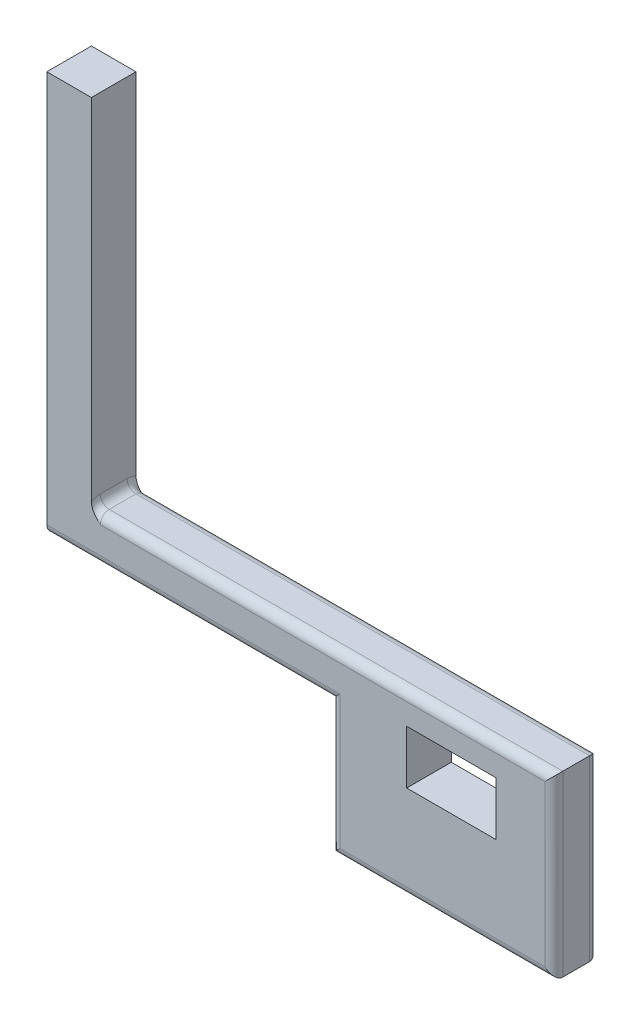
SolidWorks part; units mm, degrees
material "PE High Density"
ref_plane "Front Plane" through (0, 0, 0) normal (0, 0, 1) x (1, 0, 0)
ref_plane "Top Plane" through (0, 0, 0) normal (0, 1, 0) x (1, 0, 0)
ref_plane "Right Plane" through (0, 0, 0) normal (1, 0, 0) x (0, 0, -1)
sketch "Sketch1" plane through (0, 0, 0) normal (0, 1, 0) x (1, 0, 0)
  line L1 (0, 0) -> (5, 0)
  line L2 (0, 0) -> (0, 5)
  line L3 (0, 5) -> (5, 5)
  line L4 (5, 0) -> (5, 5)
  dimension "D1" = 5
  dimension "D2" = 5
extrude "Boss-Extrude1" add sketch "Sketch1" along normal blind 40
sketch "Sketch2" plane through (0, 0, 0) normal (0, -1, 0) x (1, 0, 0)
  line L0 (0, 0) -> (56.86, 0)
  line L1 (56.86, -5) -> (0, -5)
  line L2 (0, 0) -> (56.86, 0)
  line L3 (0, 0) -> (0, -5)
  line L4 (0, -5) -> (56.86, -5)
  line L5 (56.86, 0) -> (56.86, -5)
  line L6 (0, -5) -> (0, 0)
  line M2 (0, 0) -> (0, -5)
  line M3 (0, -5) -> (5, -5)
  line M4 (5, -5) -> (5, 0)
  line M5 (5, 0) -> (0, 0)
  dimension "D1" = 56.86
extrude "Boss-Extrude3" add sketch "Sketch2" along normal blind 5 contours L5 L0 L1 M4 | M5 M2 M3 M4
sketch "Sketch4" plane through (0, -5, 0) normal (0, -1, 0) x (1, 0, 0)
  line L0 (56.86, -5) -> (0, -5) construction
  line L1 (56.86, 0) -> (31.86, 0)
  line L2 (56.86, 0) -> (56.86, -5)
  line L3 (56.86, -5) -> (31.86, -5)
  line L4 (31.86, 0) -> (31.86, -5)
  dimension "D1" = 25
extrude "Boss-Extrude4" add sketch "Sketch4" along normal blind 15
fillet "Fillet1" radius 1 5 edges at (15.93, -5, 0) (56.86, -10, 0) (30.93, 0, 0) (31.86, -12.5, 0) (44.36, -20, 0)
fillet "Fillet2" radius 1 5 edges at (56.86, -10, -5) (30.93, 0, -5) (15.93, -5, -5) (31.86, -12.5, -5) (44.36, -20, -5)
fillet "Fillet3" radius 1 3 edges at (5, 0, -2.5) (5, -0.2929, -0.2929) (5, -0.2929, -4.7071)
sketch "Sketch5" plane through (0, 0, -5) normal (0, 0, -1) x (-1, 0, 0)
  line L0 (-6, -1) -> (-55.86, -1) construction
  line L1 (-50.36, -3.38) -> (-40.36, -3.38)
  line L2 (-50.36, -3.38) -> (-50.36, -9.38)
  line L3 (-50.36, -9.38) -> (-40.36, -9.38)
  line L4 (-40.36, -3.38) -> (-40.36, -9.38)
  line L5 (-32.86, -19) -> (-32.86, -4) construction
  dimension "D1" = 6
  dimension "D2" = 10
  dimension "D3" = 2.38
  dimension "D4" = 7.5
extrude "Cut-Extrude1" cut sketch "Sketch5" against normal through all
